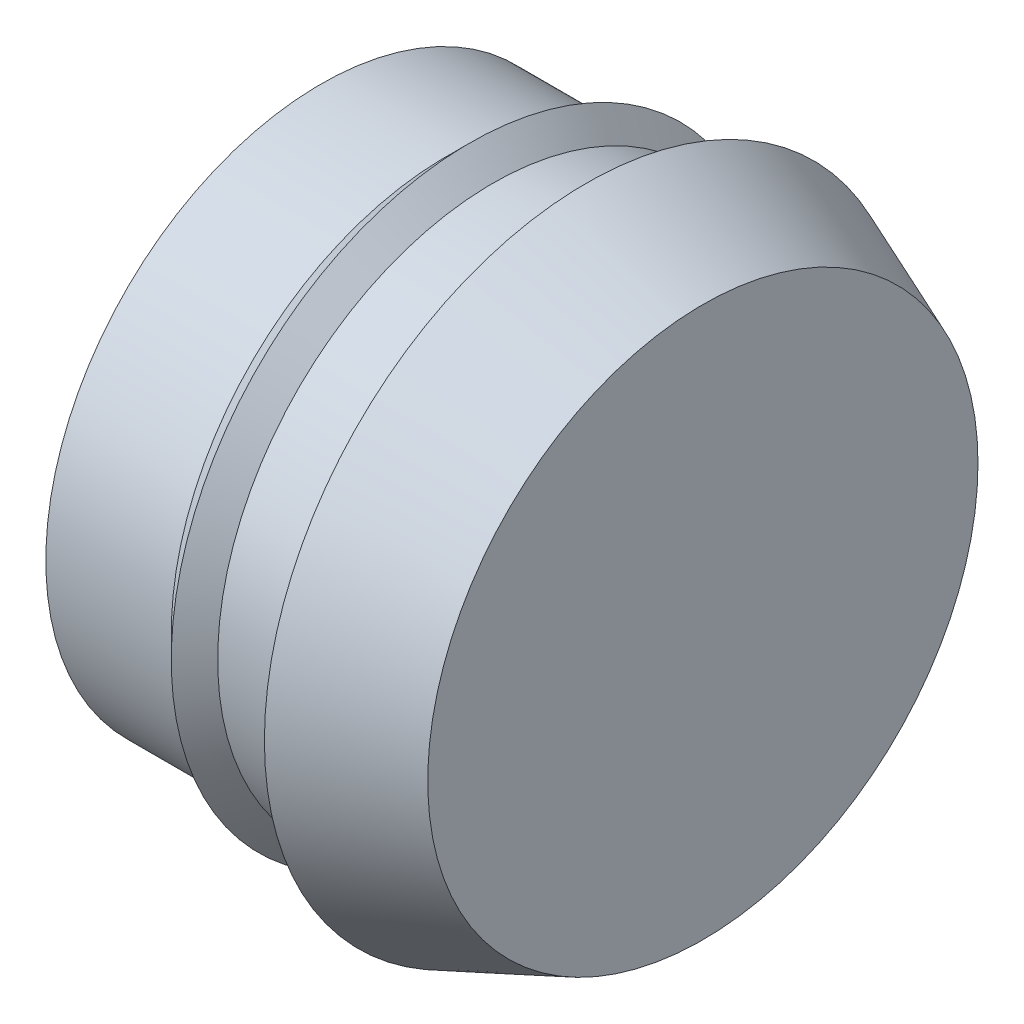
SolidWorks part; units mm, degrees
ref_plane "Front Plane" through (0, 0, 0) normal (0, 0, 1) x (1, 0, 0)
ref_plane "Top Plane" through (0, 0, 0) normal (0, 1, 0) x (1, 0, 0)
ref_plane "Right Plane" through (0, 0, 0) normal (1, 0, 0) x (0, 0, -1)
sketch "Sketch1" plane through (0, 0, 0) normal (0, 1, 0) x (1, 0, 0)
  line L0 (0, 0) -> (-13, 0)
  line L1 (0, 0) -> (0, 9.365)
  line L2 (0, 9.365) -> (-3.97, 10.955)
  line L3 (-3.97, 10.955) -> (-3.97, 9.365)
  line L4 (0, 9.365) -> (-19.3321, 9.365) construction
  line L5 (-3.97, 9.365) -> (-7.15, 9.365)
  line L6 (-7.15, 9.365) -> (-7.94, 10.155)
  line L7 (-7.94, 10.155) -> (-8.73, 9.365)
  line L8 (-8.73, 9.365) -> (-13, 9.365)
  line L9 (-13, 9.365) -> (-13, 0)
  dimension "D1" = 13
  dimension "D2" = 9.365
  dimension "D3" = 1.59
  dimension "D4" = 3.97
  dimension "D5" = 7.94
  dimension "D6" = 0.79
revolve "Revolve1" add sketch "Sketch1" angle 360 about L0
sketch "Sketch2" plane through (-13, 0, 0) normal (-1, 0, 0) x (0, 0, 1)
  circle A0 centre (0, 0) radius 9.365
  circle A1 centre (0, 0) radius 9.365 construction
  circle A2 centre (0, 0) radius 5.5
  circle A3 centre (0, 0) radius 16.51
  dimension "D1" = 11
  dimension "D2" = 33.02
equation "\"WallThick\"= 1.2'thickness of wall for printer"
equation "\"dHole\"= 3.3'diameter of screw hole"
